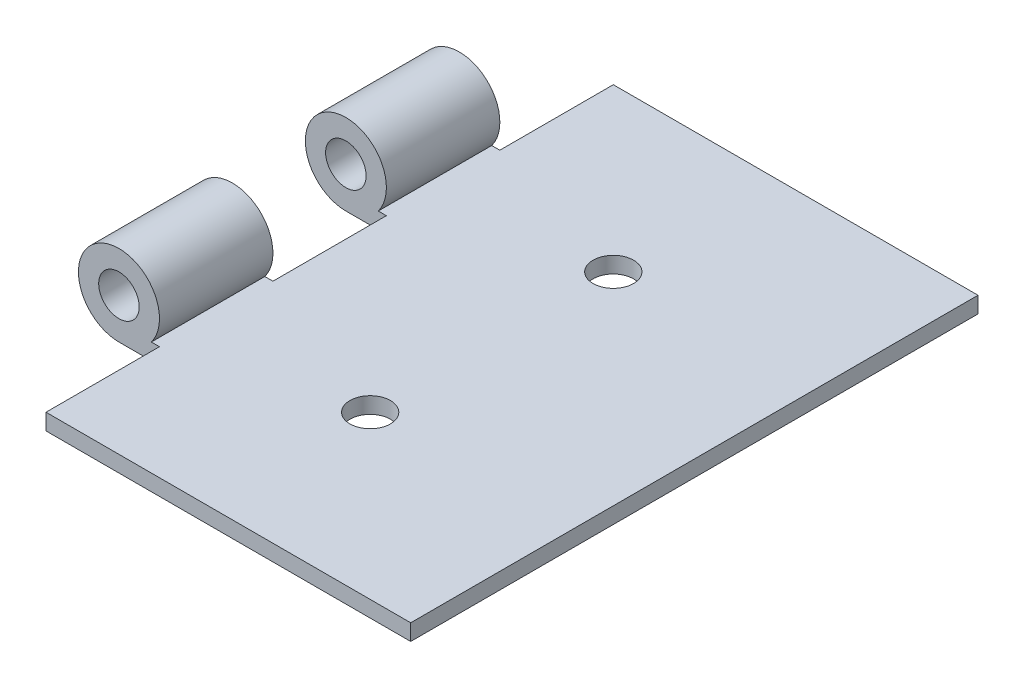
SolidWorks part; units mm, degrees
ref_plane "Front Plane" through (0, 0, 0) normal (0, 0, 1) x (1, 0, 0)
ref_plane "Top Plane" through (0, 0, 0) normal (0, 1, 0) x (1, 0, 0)
ref_plane "Right Plane" through (0, 0, 0) normal (1, 0, 0) x (0, 0, -1)
sketch "Sketch1" plane through (0, 0, 0) normal (0, 1, 0) x (1, 0, 0)
  line L1 (-25, 35) -> (25, 35)
  line L2 (-25, 35) -> (-25, -35)
  line L3 (-25, -35) -> (25, -35)
  line L4 (25, 35) -> (25, -35)
  line L5 (-25, 35) -> (25, -35) construction
  line L6 (-25, -35) -> (25, 35) construction
  point P0 (0, 0)
  dimension "D1" = 50
  dimension "D2" = 70
extrude "Boss-Extrude1" add sketch "Sketch1" along normal blind 2
sketch "Sketch2" plane through (0, 0, 35) normal (0, 0, 1) x (1, 0, 0)
  circle A0 centre (-25, 5) radius 2.5
  circle A1 centre (-25, 5) radius 5
  dimension "D1" = 10
  dimension "D2" = 5
extrude "Boss-Extrude2" add sketch "Sketch2" against normal up to surface (70 mm away) up to face at (0, 1, -35)
sketch "Sketch3" plane through (0, 2, 0) normal (0, 1, 0) x (1, 0, 0)
  line L0 (25, -35) -> (25, 35) construction
  line L1 (-21, -35) -> (25, -35) construction
  line L2 (25, 35) -> (-21, 35) construction
  circle A0 centre (0, 15) radius 2.5
  circle A1 centre (0, -15) radius 2.5
  dimension "D1" = 5
  dimension "D2" = 5
  dimension "D4" = 25
  dimension "D5" = 20
  dimension "D6" = 20
  dimension "D3" = 25
extrude "Cut-Extrude1" cut sketch "Sketch3" against normal through all
sketch "Sketch4" plane through (0, 2, 0) normal (0, 1, 0) x (1, 0, 0)
  line L0 (-20, -35) -> (-20, 35) construction
  line L1 (-30, 35) -> (-20, 35)
  line L2 (-30, 35) -> (-30, 21)
  line L3 (-30, 21) -> (-20, 21)
  line L4 (-20, 35) -> (-20, 21)
  line L5 (-30, 35) -> (-30, -35) construction
  line L6 (-30, 7) -> (-20, 7)
  line L7 (-30, 7) -> (-30, -7)
  line L8 (-30, -7) -> (-20, -7)
  line L9 (-20, 7) -> (-20, -7)
  line L11 (-30, -35) -> (-20, -35)
  line L12 (-30, -35) -> (-30, -21)
  line L13 (-30, -21) -> (-20, -21)
  line L14 (-20, -35) -> (-20, -21)
  dimension "D1" = 14
  dimension "D2" = 14
  dimension "D3" = 14
  dimension "D4" = 14
extrude "Cut-Extrude2" cut sketch "Sketch4" against normal through all both and the other way through all
